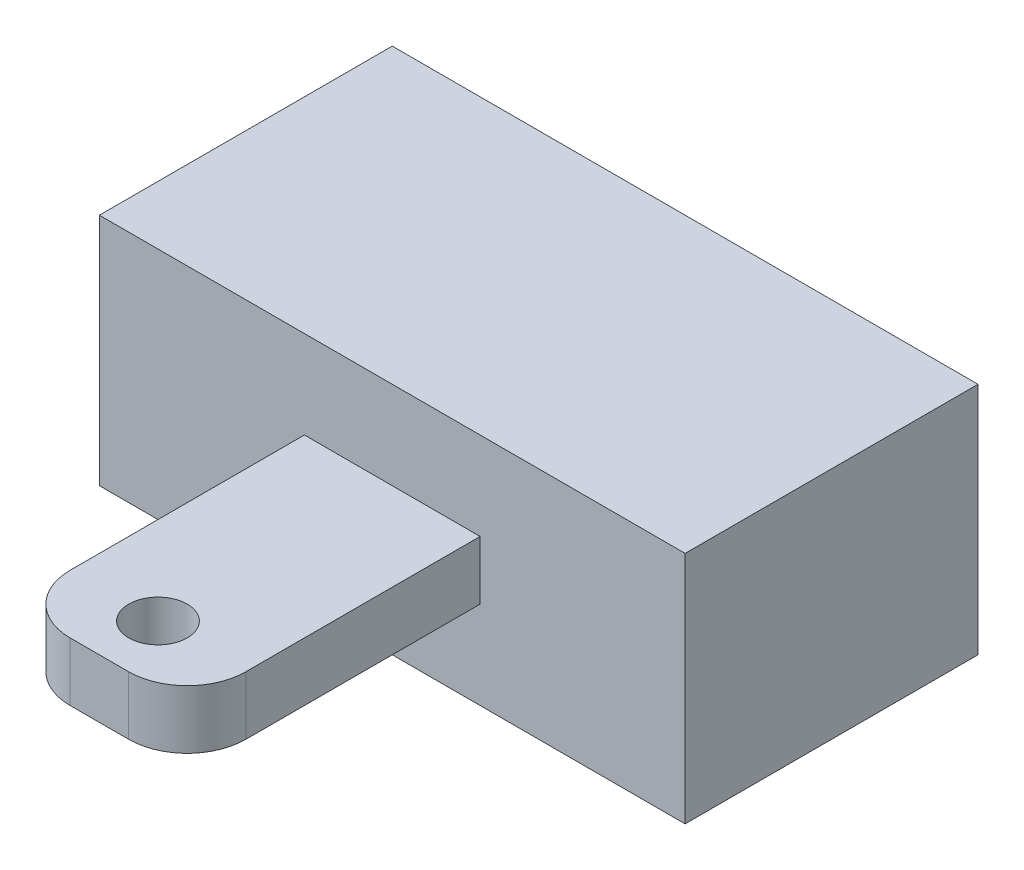
SolidWorks part; units mm, degrees
material "1060 Alloy"
ref_plane "Front Plane" through (0, 0, 0) normal (0, 0, 1) x (1, 0, 0)
ref_plane "Top Plane" through (0, 0, 0) normal (0, 1, 0) x (1, 0, 0)
ref_plane "Right Plane" through (0, 0, 0) normal (1, 0, 0) x (0, 0, -1)
sketch "Sketch1" plane through (0, 0, 0) normal (0, 1, 0) x (1, 0, 0)
  line L1 (-15, -50) -> (15, -50)
  line L2 (-15, -50) -> (-15, 50)
  line L3 (-15, 50) -> (15, 50)
  line L4 (15, -50) -> (15, 50)
  line L5 (-15, -50) -> (15, 50) construction
  line L6 (-15, 50) -> (15, -50) construction
  point P0 (0, 0)
  dimension "D1" = 30
  dimension "D2" = 100
extrude "Boss-Extrude1" add sketch "Sketch1" along normal blind 10
sketch "Sketch2" plane through (0, 10, 0) normal (0, 1, 0) x (1, 0, 0)
  line L1 (0, -5.5) -> (0, 5.5) construction
  line L2 (-15, -50) -> (15, -50) construction
  circle A1 centre (0, -40) radius 5
  dimension "D3" = 10
  dimension "D4" = 10
extrude "Cut-Extrude1" cut sketch "Sketch2" against normal blind 10
sketch "Sketch3" plane through (0, 0, -50) normal (0, 0, -1) x (-1, 0, 0)
  line L0 (-15, 10) -> (15, 10) construction
  line L1 (-50, -15) -> (50, -15)
  line L2 (-50, -15) -> (-50, 25)
  line L3 (-50, 25) -> (50, 25)
  line L4 (50, -15) -> (50, 25)
  line L5 (-50, -15) -> (50, 25) construction
  line L6 (-50, 25) -> (50, -15) construction
  line L7 (0, 5.5) -> (0, -5.5) construction
  point P0 (0, 5)
  dimension "D1" = 5
  dimension "D2" = 40
  dimension "D3" = 100
extrude "Boss-Extrude2" add sketch "Sketch3" against normal blind 50
fillet "Fillet1" radius 10 2 edges at (15, 5, 50) (-15, 5, 50)
